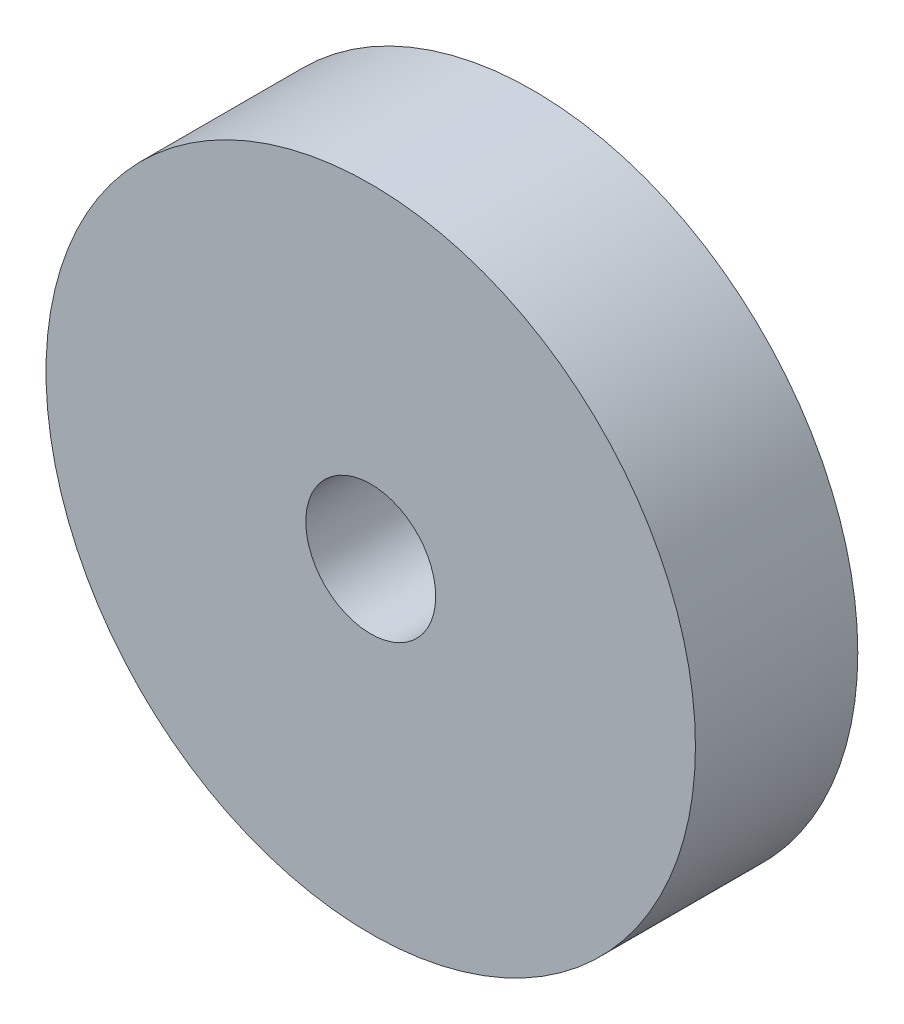
SolidWorks part; units mm, degrees
material "ABS"
ref_plane "正面" through (0, 0, 0) normal (0, 0, 1) x (1, 0, 0)
ref_plane "平面" through (0, 0, 0) normal (0, 1, 0) x (1, 0, 0)
ref_plane "右側面" through (0, 0, 0) normal (1, 0, 0) x (0, 0, -1)
sketch "ｽｹｯﾁ1" plane through (0, 0, 0) normal (0, 0, 1) x (1, 0, 0)
  circle A0 centre (0, 0) radius 1
  circle A1 centre (0, 0) radius 5
  dimension "D1" = 10
  dimension "D2" = 2
extrude "ﾎﾞｽ - 押し出し1" add sketch "ｽｹｯﾁ1" along normal blind 2.5
